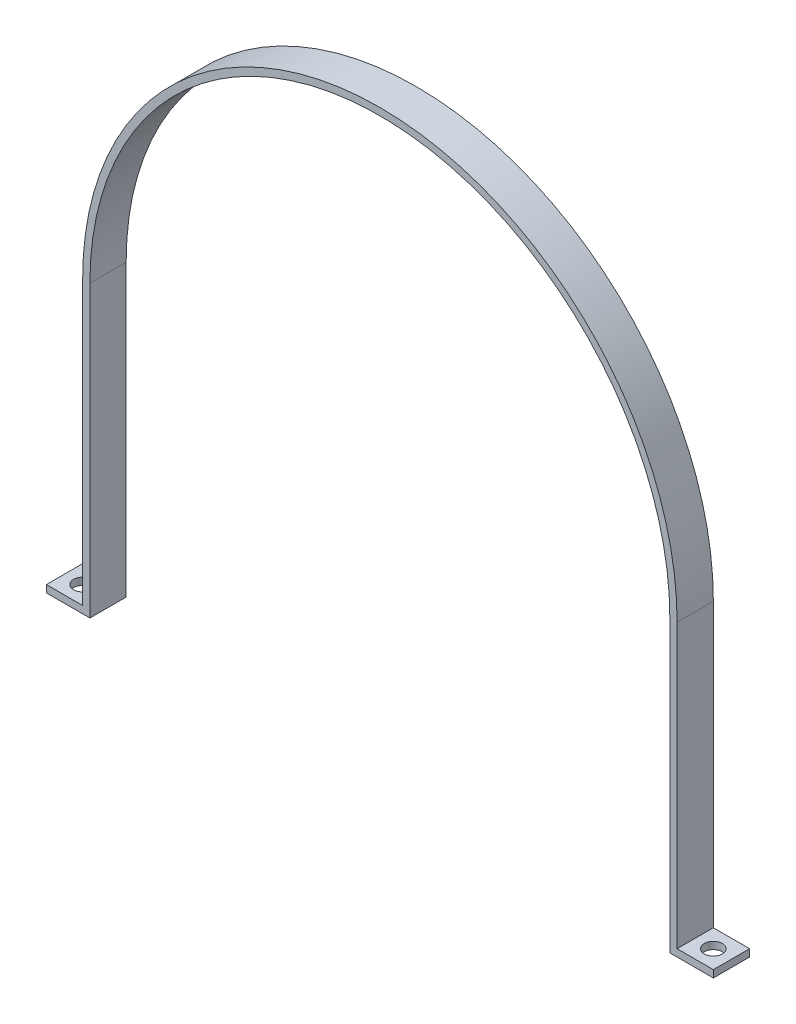
SolidWorks part; units mm, degrees
ref_plane "Ön Düzlem" through (0, 0, 0) normal (0, 0, 1) x (1, 0, 0)
ref_plane "Üst Düzlem" through (0, 0, 0) normal (0, 1, 0) x (1, 0, 0)
ref_plane "Sağ Düzlem" through (0, 0, 0) normal (1, 0, 0) x (0, 0, -1)
sketch "Çizim1" plane through (0, 0, 0) normal (0, 0, 1) x (1, 0, 0)
  line L0 (-80, 0) -> (-80, -80)
  line L2 (80, -80) -> (80, 0)
  line L3 (82, -78) -> (82, 0)
  line L4 (-82, 0) -> (-82, -78)
  line L5 (80, -80) -> (92, -80)
  line L6 (92, -80) -> (92, -78)
  line L7 (92, -78) -> (82, -78)
  line L8 (82, -80) -> (82, 0) construction
  line L9 (0, 0) -> (0, -24.6442) construction
  line L10 (-92, -78) -> (-82, -78)
  line L11 (-92, -80) -> (-92, -78)
  line L12 (-80, -80) -> (-92, -80)
  line L13 (-82, 0) -> (-82, -80) construction
  arc A0 (80, 0) -> (-80, 0) centre (0, 0) ccw
  arc A1 (82, 0) -> (-82, 0) centre (0, 0) ccw
  dimension "D1" = 160
  dimension "D2" = 2
  dimension "D3" = 12
  dimension "D4" = 2
extrude "Yükseklik-Ekstrüzyon2" add sketch "Çizim1" along normal blind 10 contours A0 L0 L12 L11 L10 L4 A1 L3 L7 L6 L5 L2
sketch "Çizim2" plane through (0, -80, 0) normal (0, -1, 0) x (1, 0, 0)
  line L0 (0, 0) -> (0, 26.9604) construction
  line L1 (-80, 0) -> (80, 0) construction
  line L2 (92, 10) -> (92, 0) construction
  circle A0 centre (87, 5) radius 2.5
  circle A1 centre (-87, 5) radius 2.5
  dimension "D1" = 5
  dimension "D2" = 5
extrude "Kes-Ekstrüzyon1" cut sketch "Çizim2" against normal blind 2
